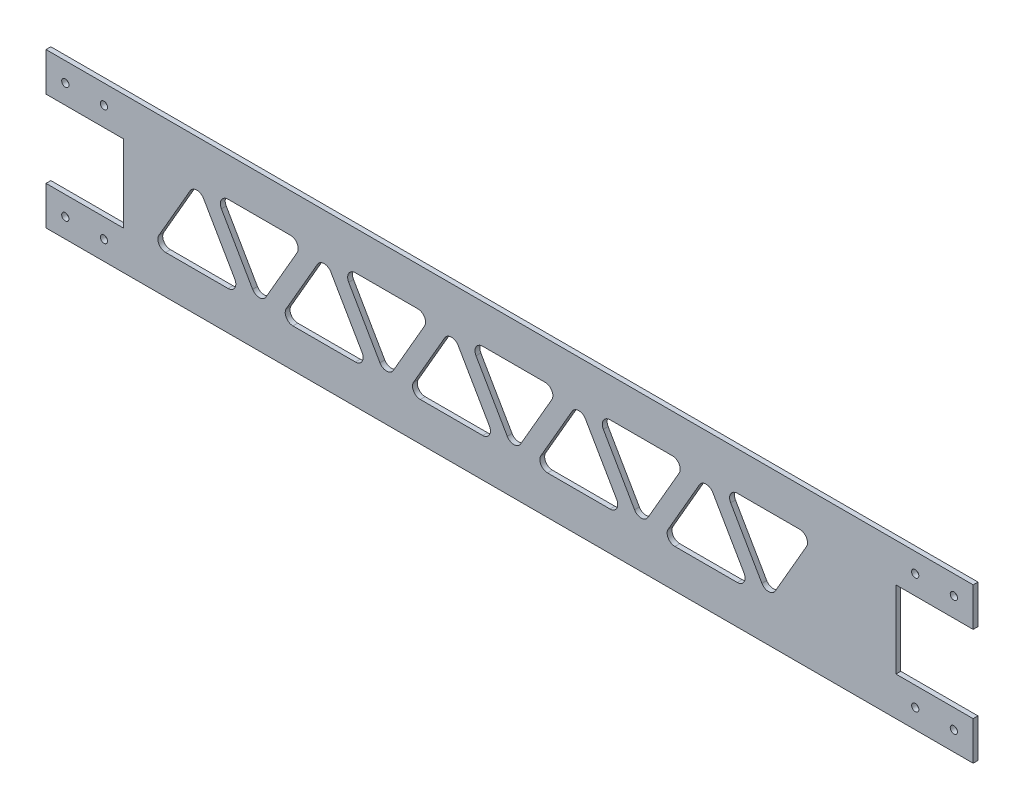
SolidWorks part; units mm, degrees
ref_plane "Front Plane" through (0, 0, 0) normal (0, 0, 1) x (1, 0, 0)
ref_plane "Top Plane" through (0, 0, 0) normal (0, 1, 0) x (1, 0, 0)
ref_plane "Right Plane" through (0, 0, 0) normal (1, 0, 0) x (0, 0, -1)
sketch "Sketch1" plane through (0, 0, 0) normal (0, 0, 1) x (1, 0, 0)
  line L1 (-304.8, 50.8) -> (304.8, 50.8)
  line L2 (-304.8, 50.8) -> (-304.8, -50.8)
  line L3 (-304.8, -50.8) -> (304.8, -50.8)
  line L4 (304.8, 50.8) -> (304.8, -50.8)
  line L5 (-304.8, 50.8) -> (304.8, -50.8) construction
  line L6 (-304.8, -50.8) -> (304.8, 50.8) construction
  point P0 (0, 0)
  dimension "D1" = 609.6
  dimension "D2" = 101.6
extrude "Boss-Extrude1" add sketch "Sketch1" along normal blind 3.175
sketch "Sketch2" plane through (0, 0, 3.175) normal (0, 0, 1) x (1, 0, 0)
  line L0 (-304.8, 50.8) -> (-304.8, -50.8) construction
  line L1 (-304.8, -50.8) -> (304.8, -50.8) construction
  line L2 (304.8, 50.8) -> (-304.8, 50.8) construction
  line L3 (0, 50.8) -> (0, -50.8) construction
  circle A0 centre (-292.1, 38.1) radius 2.3813
  circle A1 centre (-292.1, -38.1) radius 2.3813
  circle A2 centre (-266.7, 38.1) radius 2.3813
  circle A3 centre (-266.7, -38.1) radius 2.3813
  circle A4 centre (-292.1, -19.05) radius 2.3813
  circle A5 centre (-266.7, -19.05) radius 2.3813
  circle A6 centre (266.7, -19.05) radius 2.3813
  circle A7 centre (292.1, -19.05) radius 2.3813
  circle A8 centre (266.7, -38.1) radius 2.3813
  circle A9 centre (266.7, 38.1) radius 2.3813
  circle A10 centre (292.1, -38.1) radius 2.3813
  circle A11 centre (292.1, 38.1) radius 2.3813
  dimension "D9" = 4.7625
  dimension "D10" = 4.7625
  dimension "D11" = 4.7625
  dimension "D12" = 4.7625
  dimension "D13" = 4.7625
  dimension "D14" = 4.7625
  dimension "D1" = 12.7
  dimension "D2" = 25.4
  dimension "D3" = 12.7
  dimension "D4" = 38.1
  dimension "D5" = 12.7
  dimension "D6" = 12.7
  dimension "D7" = 12.7
  dimension "D8" = 12.7
  dimension "D15" = 12.7
  dimension "D16" = 19.05
  dimension "D17" = 19.05
extrude "Cut-Extrude1" cut sketch "Sketch2" against normal through all
sketch "Sketch3" plane through (0, 0, 3.175) normal (0, 0, 1) x (1, 0, 0)
  line L0 (-304.8, -50.8) -> (304.8, -50.8) construction
  line L1 (-176.2912, -25.4) -> (-205.6206, 25.4)
  line L2 (-205.6206, 25.4) -> (-234.95, -25.4)
  line L3 (-234.95, -25.4) -> (-176.2912, -25.4)
  line L4 (304.8, 50.8) -> (-304.8, 50.8) construction
  line L5 (-304.8, 50.8) -> (-304.8, -50.8) construction
  line L6 (-164.5595, -25.4) -> (-135.2301, 25.4)
  line L7 (-135.2301, 25.4) -> (-193.8888, 25.4)
  line L8 (-193.8888, 25.4) -> (-164.5595, -25.4)
  line L9 (-92.5836, -25.4) -> (-121.913, 25.4)
  line L10 (-121.913, 25.4) -> (-151.2424, -25.4)
  line L11 (-151.2424, -25.4) -> (-92.5836, -25.4)
  line L12 (-80.8519, -25.4) -> (-51.5225, 25.4)
  line L13 (-51.5225, 25.4) -> (-110.1813, 25.4)
  line L14 (-110.1813, 25.4) -> (-80.8519, -25.4)
  line L15 (-8.876, -25.4) -> (-38.2054, 25.4)
  line L16 (-38.2054, 25.4) -> (-67.5348, -25.4)
  line L17 (-67.5348, -25.4) -> (-8.876, -25.4)
  line L18 (2.8557, -25.4) -> (32.1851, 25.4)
  line L19 (32.1851, 25.4) -> (-26.4737, 25.4)
  line L20 (-26.4737, 25.4) -> (2.8557, -25.4)
  line L21 (74.8316, -25.4) -> (45.5022, 25.4)
  line L22 (45.5022, 25.4) -> (16.1728, -25.4)
  line L23 (16.1728, -25.4) -> (74.8316, -25.4)
  line L24 (86.5633, -25.4) -> (115.8927, 25.4)
  line L25 (115.8927, 25.4) -> (57.2339, 25.4)
  line L26 (57.2339, 25.4) -> (86.5633, -25.4)
  line L27 (158.5392, -25.4) -> (129.2098, 25.4)
  line L28 (129.2098, 25.4) -> (99.8804, -25.4)
  line L29 (99.8804, -25.4) -> (158.5392, -25.4)
  line L30 (170.2709, -25.4) -> (199.6003, 25.4)
  line L31 (199.6003, 25.4) -> (140.9415, 25.4)
  line L32 (140.9415, 25.4) -> (170.2709, -25.4)
  circle A0 centre (-205.6206, -8.4667) radius 16.9333 construction
  circle A1 centre (-164.5595, 8.4667) radius 16.9333 construction
  circle A2 centre (-121.913, -8.4667) radius 16.9333 construction
  circle A3 centre (-80.8519, 8.4667) radius 16.9333 construction
  circle A4 centre (-38.2054, -8.4667) radius 16.9333 construction
  circle A5 centre (2.8557, 8.4667) radius 16.9333 construction
  circle A6 centre (45.5022, -8.4667) radius 16.9333 construction
  circle A7 centre (86.5633, 8.4667) radius 16.9333 construction
  circle A8 centre (129.2098, -8.4667) radius 16.9333 construction
  circle A9 centre (170.2709, 8.4667) radius 16.9333 construction
  dimension "D1" = 25.4
  dimension "D2" = 25.4
  dimension "D3" = 25.4
  dimension "D4" = 25.4
  dimension "D5" = 10.16
  dimension "D6" = 69.85
  dimension "D7" = 5
extrude "Cut-Extrude2" cut sketch "Sketch3" against normal through all
fillet "Fillet1" radius 5.08 30 edges at (170.2709, -25.4, 1.5875) (199.6003, 25.4, 1.5875) (140.9415, 25.4, 1.5875) (129.2098, 25.4, 1.5875) (99.8804, -25.4, 1.5875) (158.5392, -25.4, 1.5875) (57.2339, 25.4, 1.5875) (86.5633, -25.4, 1.5875) (115.8927, 25.4, 1.5875) (32.1851, 25.4, 1.5875) (45.5022, 25.4, 1.5875) (16.1728, -25.4, 1.5875) (74.8316, -25.4, 1.5875) (2.8557, -25.4, 1.5875) (-26.4737, 25.4, 1.5875) (-67.5348, -25.4, 1.5875) (-8.876, -25.4, 1.5875) (-38.2054, 25.4, 1.5875) (-80.8519, -25.4, 1.5875) (-51.5225, 25.4, 1.5875) (-110.1813, 25.4, 1.5875) (-121.913, 25.4, 1.5875) (-92.5836, -25.4, 1.5875) (-151.2424, -25.4, 1.5875) (-135.2301, 25.4, 1.5875) (-193.8888, 25.4, 1.5875) (-176.2912, -25.4, 1.5875) (-164.5595, -25.4, 1.5875) (-234.95, -25.4, 1.5875) (-205.6206, 25.4, 1.5875)
sketch "Sketch4" plane through (0, 0, 3.175) normal (0, 0, 1) x (1, 0, 0)
  line L0 (-304.8, 50.8) -> (-304.8, -50.8) construction
  line L1 (-304.8, 25.4) -> (-254, 25.4)
  line L2 (-304.8, 25.4) -> (-304.8, -25.4)
  line L3 (-304.8, -25.4) -> (-254, -25.4)
  line L4 (-254, 25.4) -> (-254, -25.4)
  line L5 (304.8, 50.8) -> (-304.8, 50.8) construction
  line L6 (-304.8, -50.8) -> (304.8, -50.8) construction
  line L7 (304.8, -50.8) -> (304.8, 50.8) construction
  line L8 (304.8, 25.4) -> (254, 25.4)
  line L9 (304.8, 25.4) -> (304.8, -25.4)
  line L10 (304.8, -25.4) -> (254, -25.4)
  line L11 (254, 25.4) -> (254, -25.4)
  dimension "D1" = 50.8
  dimension "D2" = 25.4
  dimension "D3" = 25.4
  dimension "D4" = 50.8
  dimension "D5" = 25.4
  dimension "D6" = 50.8
extrude "Cut-Extrude3" cut sketch "Sketch4" against normal through all
